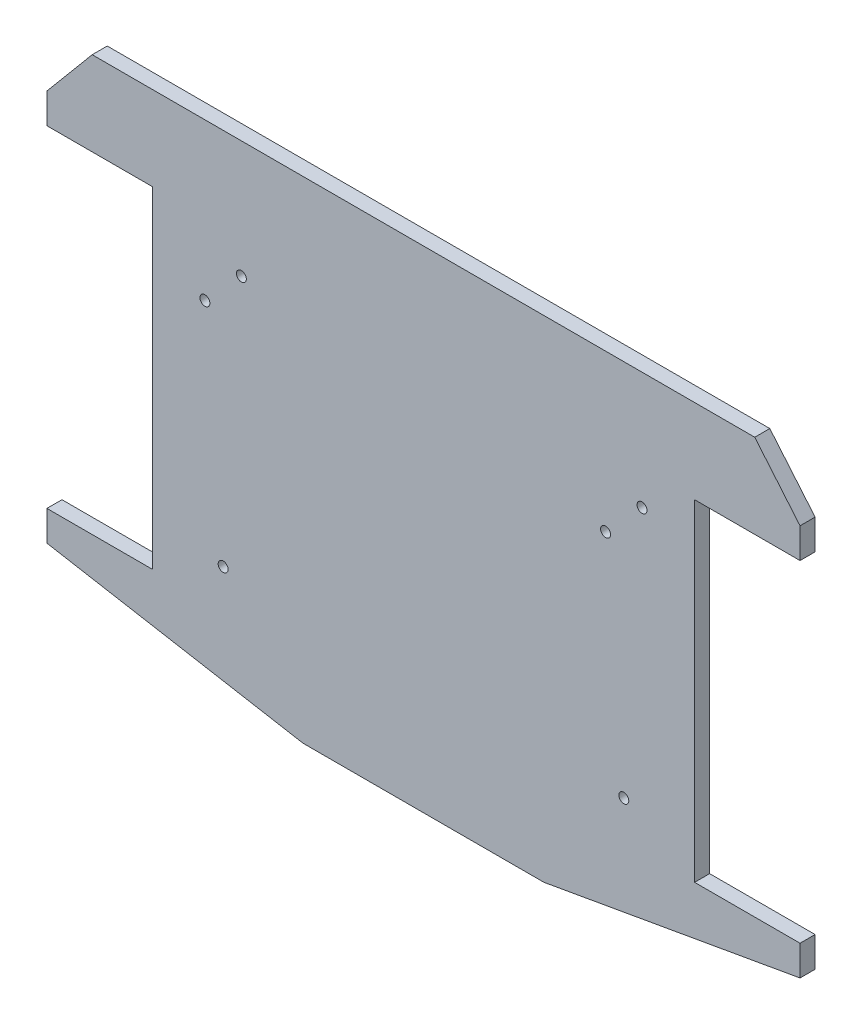
SolidWorks part; units mm, degrees
ref_plane "Front" through (0, 0, 0) normal (0, 0, 1) x (1, 0, 0)
ref_plane "Top" through (0, 0, 0) normal (0, 1, 0) x (1, 0, 0)
ref_plane "Right" through (0, 0, 0) normal (1, 0, 0) x (0, 0, -1)
sketch "Эскиз1" plane through (139.7252, 79.9452, 32.4678) normal (0, 0, -1) x (-1, 0, 0)
  line L10 (-144.3372, 75.3108) -> (-144.3372, 60.3108) construction
  line L16 (-54.3372, 85.3108) -> (-54.3372, 195.3108)
  line L17 (-54.3372, 195.3108) -> (-19.3372, 195.3108)
  line L18 (-54.3372, 85.3108) -> (-19.3372, 85.3108)
  line L19 (-19.3372, 85.3108) -> (-19.3372, 75.3108)
  line L20 (-234.3372, 85.3108) -> (-234.3372, 195.3108)
  line L21 (-234.3372, 195.3108) -> (-269.3372, 195.3108)
  line L22 (-269.3372, 195.3108) -> (-269.3372, 205.3108)
  line L24 (-19.3372, 205.3108) -> (-19.3372, 195.3108)
  line L25 (-234.3372, 85.3108) -> (-269.3372, 85.3108)
  line L26 (-269.3372, 85.3108) -> (-269.3372, 75.3108)
  line L27 (-269.3372, 75.3108) -> (-19.3372, 75.3108) construction
  line L28 (-184.3372, 60.3108) -> (-104.3372, 60.3108)
  line L29 (-19.3372, 75.3108) -> (-104.3372, 60.3108)
  line L30 (-184.3372, 60.3108) -> (-269.3372, 75.3108)
  line L31 (-269.3372, 205.3108) -> (-254.3056, 223.2525)
  line L32 (-269.3372, 205.3108) -> (-169.3372, 324.6711) construction
  line L33 (-254.3056, 223.2525) -> (-34.3688, 223.2525)
  line L34 (-119.3372, 324.6711) -> (-19.3372, 205.3108) construction
  line L35 (-34.3688, 223.2525) -> (-19.3372, 205.3108)
  point P19 (-144.3372, 60.3108)
  dimension "D1" = 110
  dimension "D2" = 35
  dimension "D3" = 10
  dimension "D4" = 10
  dimension "D5" = 35
  dimension "D6" = 10
  dimension "D7" = 110
  dimension "D8" = 15
extrude "Бобышка-Вытянуть2" add sketch "Эскиз1" along normal blind 5
sketch "Эскиз3" plane through (0, 0, 27.4678) normal (0, 0, -1) x (-1, 0, 0)
  circle A0 centre (-217.5624, 177.756) radius 1.65 construction
  circle A1 centre (-350.5624, 177.756) radius 1.65 construction
  circle A2 centre (-356.6141, 264.256) radius 1.65 construction
  circle A3 centre (-344.5107, 251.256) radius 1.65 construction
  circle A4 centre (-211.5107, 251.256) radius 1.65 construction
  circle A5 centre (-223.6141, 264.256) radius 1.65 construction
  circle A6 centre (-217.5624, 177.756) radius 1.65
  circle A7 centre (-350.5624, 177.756) radius 1.65
  circle A8 centre (-356.6141, 264.256) radius 1.65
  circle A9 centre (-344.5107, 251.256) radius 1.65
  circle A10 centre (-211.5107, 251.256) radius 1.65
  circle A11 centre (-223.6141, 264.256) radius 1.65
extrude "Вырез-Вытянуть1" cut sketch "Эскиз3" against normal blind 10
